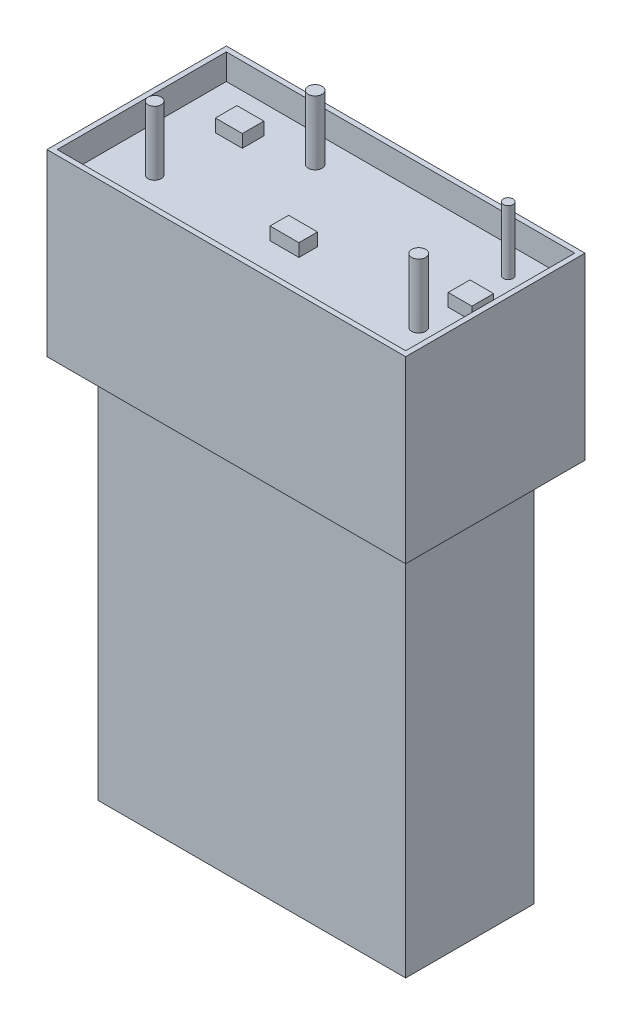
SolidWorks part; units mm, degrees
ref_plane "Front Plane" through (0, 0, 0) normal (0, 0, 1) x (1, 0, 0)
ref_plane "Top Plane" through (0, 0, 0) normal (0, 1, 0) x (1, 0, 0)
ref_plane "Right Plane" through (0, 0, 0) normal (1, 0, 0) x (0, 0, -1)
sketch "Sketch1" plane through (0, 0, 0) normal (0, 1, 0) x (1, 0, 0)
  line L1 (-6000, -2500) -> (6000, -2500)
  line L2 (-6000, -2500) -> (-6000, 2500)
  line L3 (-6000, 2500) -> (6000, 2500)
  line L4 (6000, -2500) -> (6000, 2500)
  line L5 (-6000, -2500) -> (6000, 2500) construction
  line L6 (-6000, 2500) -> (6000, -2500) construction
  point P0 (0, 0)
  dimension "D1" = 12000
  dimension "D2" = 5000
extrude "Boss-Extrude1" add sketch "Sketch1" along normal blind 15000
sketch "Sketch2" plane through (0, 15000, 0) normal (0, 1, 0) x (1, 0, 0)
  line L1 (-7000, -3500) -> (7000, -3500)
  line L2 (-7000, -3500) -> (-7000, 3500)
  line L3 (-7000, 3500) -> (7000, 3500)
  line L4 (7000, -3500) -> (7000, 3500)
  line L5 (-7000, -3500) -> (7000, 3500) construction
  line L6 (-7000, 3500) -> (7000, -3500) construction
  point P0 (0, 0)
  dimension "D1" = 14000
  dimension "D2" = 7000
extrude "Boss-Extrude2" add sketch "Sketch2" along normal blind 6000
sketch "Sketch3" plane through (0, 21000, 0) normal (0, 1, 0) x (1, 0, 0)
  line L0 (6800, -3300) -> (6800, 3300)
  line L1 (6800, 3300) -> (-6800, 3300)
  line L2 (-6800, 3300) -> (-6800, -3300)
  line L3 (-6800, -3300) -> (6800, -3300)
  line L4 (7000, -3500) -> (7000, 3500)
  line L5 (7000, 3500) -> (-7000, 3500)
  line L6 (-7000, 3500) -> (-7000, -3500)
  line L7 (-7000, -3500) -> (7000, -3500)
  line L8 (7000, -3500) -> (7000, 3500)
  line L9 (7000, 3500) -> (-7000, 3500)
  line L10 (-7000, 3500) -> (-7000, -3500)
  line L11 (-7000, -3500) -> (7000, -3500)
  dimension "D1" = 0
  dimension "D2" = 200
extrude "Boss-Extrude3" add sketch "Sketch3" along normal blind 1000
sketch "Sketch4" plane through (0, 21000, 0) normal (0, 1, 0) x (1, 0, 0)
  line L1 (-5279.1612, 1353.4428) -> (-4229.1921, 1353.4428)
  line L2 (-5279.1612, 1353.4428) -> (-5279.1612, 2193.6628)
  line L3 (-5279.1612, 2193.6628) -> (-4229.1921, 2193.6628)
  line L4 (-4229.1921, 1353.4428) -> (-4229.1921, 2193.6628)
  line L5 (-5279.1612, 1353.4428) -> (-4229.1921, 2193.6628) construction
  line L6 (-5279.1612, 2193.6628) -> (-4229.1921, 1353.4428) construction
  line L7 (-563.9392, -505.0632) -> (563.9392, -505.0632)
  line L8 (-563.9392, -505.0632) -> (-563.9392, -1230.2639)
  line L9 (-563.9392, -1230.2639) -> (563.9392, -1230.2639)
  line L10 (563.9392, -505.0632) -> (563.9392, -1230.2639)
  line L11 (-563.9392, -505.0632) -> (563.9392, -1230.2639) construction
  line L12 (-563.9392, -1230.2639) -> (563.9392, -505.0632) construction
  line L13 (5159.11, 848.7174) -> (6083.9377, 848.7174)
  line L14 (5159.11, 848.7174) -> (5159.11, 0)
  line L15 (5159.11, 0) -> (6083.9377, 0)
  line L16 (6083.9377, 848.7174) -> (6083.9377, 0)
  line L17 (5159.11, 848.7174) -> (6083.9377, 0) construction
  line L18 (5159.11, 0) -> (6083.9377, 848.7174) construction
  point P0 (-4754.1766, 1773.5528)
  point P5 (0, -867.6635)
  point P10 (5621.5238, 424.3587)
extrude "Boss-Extrude4" add sketch "Sketch4" along normal blind 500
sketch "Sketch5" plane through (0, 21000, 0) normal (0, 1, 0) x (1, 0, 0)
  circle A0 centre (-2270.0956, 2238.3732) radius 271.9312
  circle A1 centre (5262.8487, -1254.6124) radius 273.5484
  circle A2 centre (-5042.3581, -1254.6124) radius 258.0723
  circle A3 centre (5262.8487, 2238.3732) radius 190.9495
extrude "Boss-Extrude5" add sketch "Sketch5" along normal blind 2500
